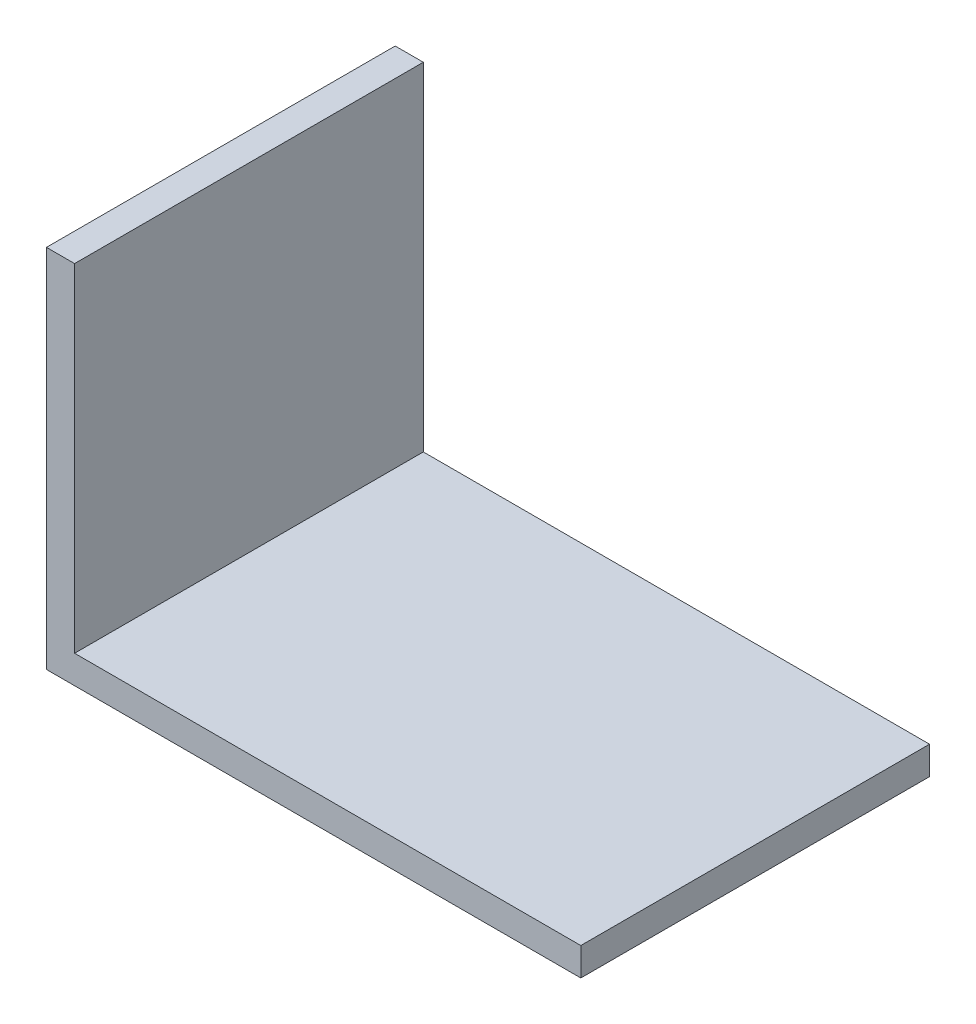
SolidWorks part; units mm, degrees
ref_plane "Front Plane" through (0, 0, 0) normal (0, 0, 1) x (1, 0, 0)
ref_plane "Top Plane" through (0, 0, 0) normal (0, 1, 0) x (1, 0, 0)
ref_plane "Right Plane" through (0, 0, 0) normal (1, 0, 0) x (0, 0, -1)
sketch "Sketch1" plane through (0, 0, 0) normal (1, 0, 0) x (0, 0, -1)
  line L1 (15.5, -15) -> (-15.5, -15)
  line L2 (15.5, -15) -> (15.5, 15)
  line L3 (15.5, 15) -> (-15.5, 15)
  line L4 (-15.5, -15) -> (-15.5, 15)
  line L5 (15.5, -15) -> (-15.5, 15) construction
  line L6 (15.5, 15) -> (-15.5, -15) construction
  point P0 (0, 0)
  dimension "D1" = 31
  dimension "D2" = 30
extrude "Boss-Extrude1" add sketch "Sketch1" along normal blind 2.5
sketch "Sketch2" plane through (0, 0, 0) normal (1, 0, 0) x (0, 0, -1)
  line L1 (-15.5, -15) -> (15.5, -15)
  line L2 (-15.5, -15) -> (-15.5, -17.5)
  line L3 (-15.5, -17.5) -> (15.5, -17.5)
  line L4 (15.5, -15) -> (15.5, -17.5)
  dimension "D1" = 2.5
extrude "Boss-Extrude2" add sketch "Sketch2" along normal blind 47.5
